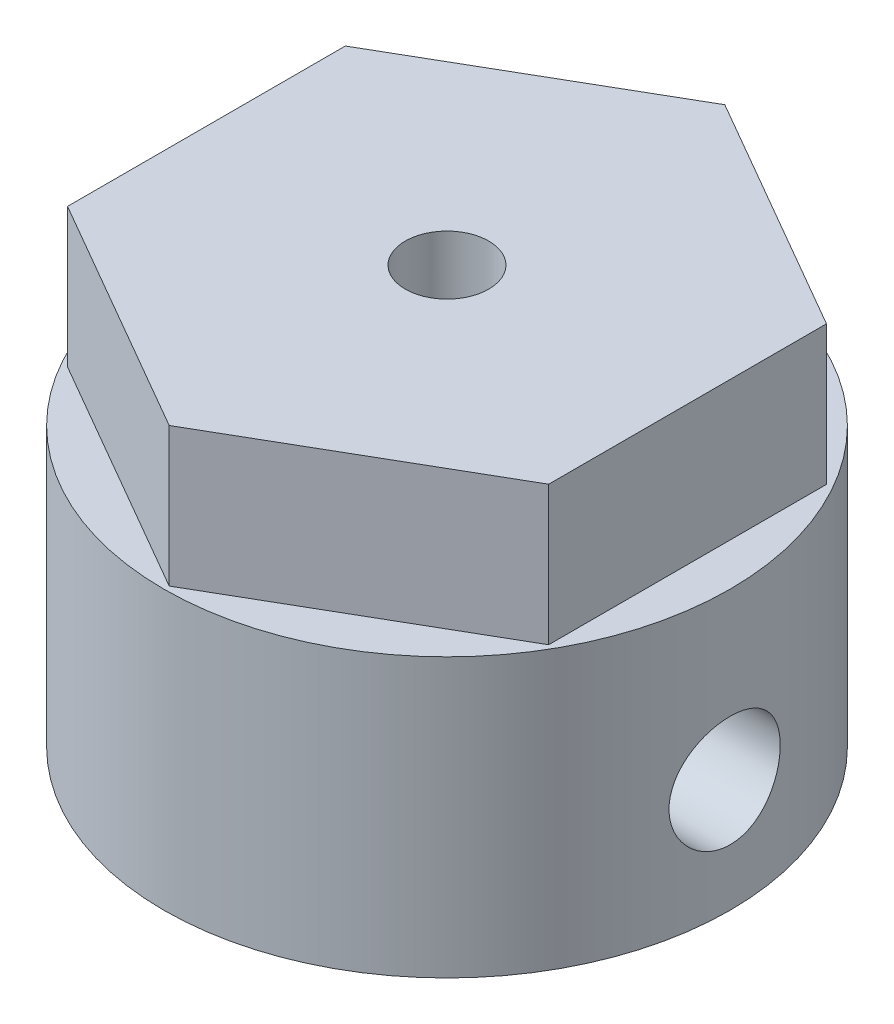
SolidWorks part; units mm, degrees
ref_plane "Спереди" through (0, 0, 0) normal (0, 0, 1) x (1, 0, 0)
ref_plane "Сверху" through (0, 0, 0) normal (0, 1, 0) x (1, 0, 0)
ref_plane "Справа" through (0, 0, 0) normal (1, 0, 0) x (0, 0, -1)
sketch "Эскиз1" plane through (0, 0, 0) normal (0, 1, 0) x (1, 0, 0)
  circle A0 centre (0, 0) radius 10.18
extrude "тело" add sketch "Эскиз1" along normal blind 10
sketch "Эскиз2" plane through (0, 10, 0) normal (0, 1, 0) x (1, 0, 0)
  line L1 (0, 9.9882) -> (-8.65, 4.9941)
  line L2 (-8.65, 4.9941) -> (-8.65, -4.9941)
  line L3 (-8.65, -4.9941) -> (0, -9.9882)
  line L4 (0, -9.9882) -> (8.65, -4.9941)
  line L5 (8.65, -4.9941) -> (8.65, 4.9941)
  line L6 (8.65, 4.9941) -> (0, 9.9882)
  circle A0 centre (0, 0) radius 8.65 construction
  dimension "D1" = 17.3
extrude "шестигранник" add sketch "Эскиз2" along normal blind 5
sketch "Эскиз3" plane through (0, 0, 0) normal (0, -1, 0) x (1, 0, 0)
  circle A0 centre (0, 0) radius 2
  dimension "D1" = 4
extrude "отверстие под ось" cut sketch "Эскиз3" against normal blind 8.6
sketch "Эскиз4" plane through (0, 0, 0) normal (0, -1, 0) x (1, 0, 0)
  line L0 (0, 0) -> (-2.5, -4.3301) construction
  line L1 (0, 0) -> (5, 0) construction
  line L2 (-5.1726, -1.4592) -> (1.3226, -5.2092)
  line L3 (-5.1726, -1.4592) -> (-6.3226, -3.4511)
  line L4 (1.3226, -5.2092) -> (0.1726, -7.2011)
  line L5 (-6.3226, -3.4511) -> (0.1726, -7.2011)
  line L6 (3.85, 3.75) -> (6.15, 3.75)
  line L7 (3.85, 3.75) -> (3.85, -3.75)
  line L8 (6.15, 3.75) -> (6.15, -3.75)
  line L9 (3.85, -3.75) -> (6.15, -3.75)
  line L10 (-6.3226, -3.4511) -> (1.3226, -5.2092) construction
  line L11 (-5.1726, -1.4592) -> (0.1726, -7.2011) construction
  line L12 (6.15, 3.75) -> (3.85, -3.75) construction
  line L13 (3.85, 3.75) -> (6.15, -3.75) construction
  point P3 (-7.027, -9.7927)
  point P6 (-2.5, -4.3301)
  point P7 (-3.6687, -4.8023)
  dimension "D1" = 5
  dimension "D2" = 7.5
  dimension "D3" = 2.3
  dimension "D4" = 120
extrude "пазы под гайки" cut sketch "Эскиз4" against normal blind 8
sketch "Эскиз5" plane through (3.85, 0, 0) normal (1, 0, 0) x (0, 0, -1)
  line L0 (0, 0) -> (0, 4.0415) construction
  line L2 (0, 0) -> (3.5, 2.0207) construction
  line L3 (3.5, 2.0207) -> (3.5, 6.0622) construction
  line L4 (3.5, 6.0622) -> (0, 8.0829) construction
  line L5 (0, 8.0829) -> (-3.5, 6.0622) construction
  line L6 (-3.5, 6.0622) -> (-3.5, 2.0207) construction
  line L7 (-3.5, 2.0207) -> (0, 0) construction
  circle A0 centre (0, 4.0415) radius 3.5 construction
  circle A1 centre (0, 4.0415) radius 2
  dimension "D1" = 4
  dimension "D2" = 7
extrude "отверстие чтоб прикрутить 1" cut sketch "Эскиз5" along normal through all and the other way up to surface other way up to face at (0, 8.6, -2)
sketch "Эскиз6" plane through (-1.925, 0, -3.3342) normal (-0.5, 0, -0.866) x (-0.866, 0, 0.5)
  line L0 (0, 0) -> (0, 4.0415) construction
  line L2 (0, 0) -> (3.5, 2.0207) construction
  line L3 (3.5, 2.0207) -> (3.5, 6.0622) construction
  line L4 (3.5, 6.0622) -> (0, 8.0829) construction
  line L5 (0, 8.0829) -> (-3.5, 6.0622) construction
  line L6 (-3.5, 6.0622) -> (-3.5, 2.0207) construction
  line L7 (-3.5, 2.0207) -> (0, 0) construction
  circle A0 centre (0, 4.0415) radius 3.5 construction
  circle A1 centre (0, 4.0415) radius 2
  dimension "D1" = 4
  dimension "D2" = 7
extrude "отверстие чтоб прикрутить 2" cut sketch "Эскиз6" along normal through all and the other way up to surface other way up to face at (0, 0, -2)
sketch "Эскиз7" plane through (3.85, 0, 0) normal (1, 0, 0) x (0, 0, -1)
  line L1 (-3.75, 1.8764) -> (0, -0.2887)
  line L2 (0, -0.2887) -> (3.75, 1.8764)
  line L3 (3.75, 1.8764) -> (3.75, 6.2065)
  line L4 (3.75, 6.2065) -> (0, 8.3716)
  line L5 (0, 8.3716) -> (-3.75, 6.2065)
  line L6 (-3.75, 6.2065) -> (-3.75, 1.8764)
  circle A0 centre (0, 4.0415) radius 3.75 construction
  circle A1 centre (0, 4.0415) radius 2 construction
  dimension "D1" = 7.5
extrude "паз для гайки 1" cut sketch "Эскиз7" along normal up to surface (2.3 mm away) up to face at (6.15, 4.0415, -2)
sketch "Эскиз8" plane through (-1.925, 0, -3.3342) normal (-0.5, 0, -0.866) x (-0.866, 0, 0.5)
  line L1 (0, 8.3716) -> (-3.75, 6.2065)
  line L2 (-3.75, 6.2065) -> (-3.75, 1.8764)
  line L3 (-3.75, 1.8764) -> (0, -0.2887)
  line L4 (0, -0.2887) -> (3.75, 1.8764)
  line L5 (3.75, 1.8764) -> (3.75, 6.2065)
  line L6 (3.75, 6.2065) -> (0, 8.3716)
  circle A0 centre (0, 4.0415) radius 3.75 construction
  circle A1 centre (0, 4.0415) radius 2 construction
  dimension "D1" = 7.5
extrude "паз для гайки 2" cut sketch "Эскиз8" along normal up to surface (2.3 mm away) up to face at (-4.8071, 4.0415, -4.3261)
sketch "Эскиз9" plane through (0, 15, 0) normal (0, 1, 0) x (1, 0, 0)
  circle A0 centre (0, 0) radius 1.5
  dimension "D1" = 3
extrude "Вырез-Вытянуть7" cut sketch "Эскиз9" against normal through all
